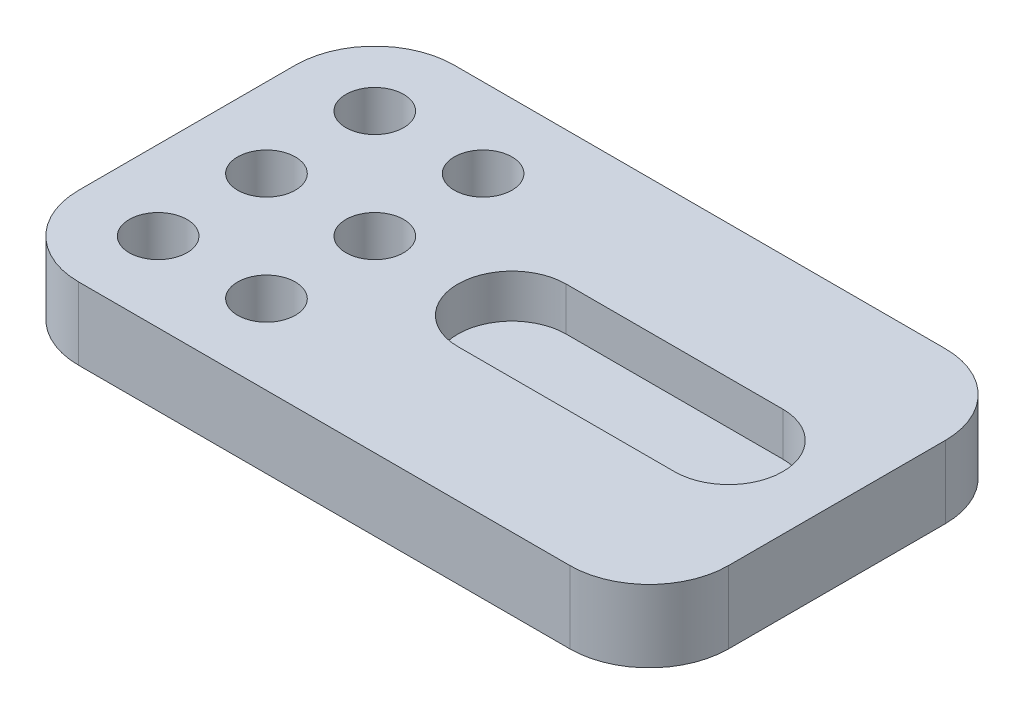
SolidWorks part; units mm, degrees
ref_plane "Front Plane" through (0, 0, 0) normal (0, 0, 1) x (1, 0, 0)
ref_plane "Top Plane" through (0, 0, 0) normal (0, 1, 0) x (1, 0, 0)
ref_plane "Right Plane" through (0, 0, 0) normal (1, 0, 0) x (0, 0, -1)
sketch "Sketch1" plane through (0, 0, 0) normal (0, 1, 0) x (1, 0, 0)
  line L1 (-90, 52) -> (90, 52)
  line L2 (-90, 52) -> (-90, -52)
  line L3 (-90, -52) -> (90, -52)
  line L4 (90, 52) -> (90, -52)
  line L5 (-90, 52) -> (90, -52) construction
  line L6 (-90, -52) -> (90, 52) construction
  point P0 (0, 0)
  dimension "D1" = 104
  dimension "D2" = 180
extrude "Boss-Extrude1" add sketch "Sketch1" along normal blind 20
fillet "Fillet1" radius 22 4 edges at (90, 10, -52) (90, 10, 52) (-90, 10, 52) (-90, 10, -52)
sketch "Sketch3" plane through (0, 20, 0) normal (0, 1, 0) x (1, 0, 0)
  line L0 (-81.0432, 30) -> (-31.8511, 30) construction
  line L1 (68, 52) -> (-68, 52) construction
  line L2 (-78.5659, 0) -> (-31.8511, 0) construction
  line L3 (-78.5659, -30) -> (-31.8511, -30) construction
  line L4 (-68, 42.9989) -> (-68, -43.3789) construction
  line L5 (-38, 44.9596) -> (-38, -44.9596) construction
  line L6 (-90, 30) -> (-90, -30) construction
  line L7 (-68, -52) -> (68, -52) construction
  circle A0 centre (-68, 30) radius 8
  circle A1 centre (-68, 0) radius 8
  circle A2 centre (-68, -30) radius 8
  circle A3 centre (-38, -30) radius 8
  circle A4 centre (-38, 0) radius 8
  circle A5 centre (-38, 30) radius 8
  point P30 (0, 0)
  point P31 (0, 0)
  dimension "D6" = 16
  dimension "D7" = 68
  dimension "D1" = 22
  dimension "D2" = 22
  dimension "D3" = 30
  dimension "D4" = 22
  dimension "D5" = 30
extrude "Cut-Extrude1" cut sketch "Sketch3" against normal blind 20
sketch "Sketch4" plane through (0, 20, 0) normal (0, 1, 0) x (1, 0, 0)
  line L0 (0, 0) -> (60, 0) construction
  line L1 (0, 15) -> (60, 15)
  line L2 (0, -15) -> (60, -15)
  arc A0 (0, 15) -> (0, -15) centre (0, 0) ccw
  arc A1 (60, -15) -> (60, 15) centre (60, 0) ccw
  point P3 (30, 0)
  point P10 (-0.0321, -0.0092)
  dimension "D1" = 15
  dimension "D2" = 60
extrude "Cut-Extrude2" cut sketch "Sketch4" against normal blind 12 contours L2 A1 L1 A0
